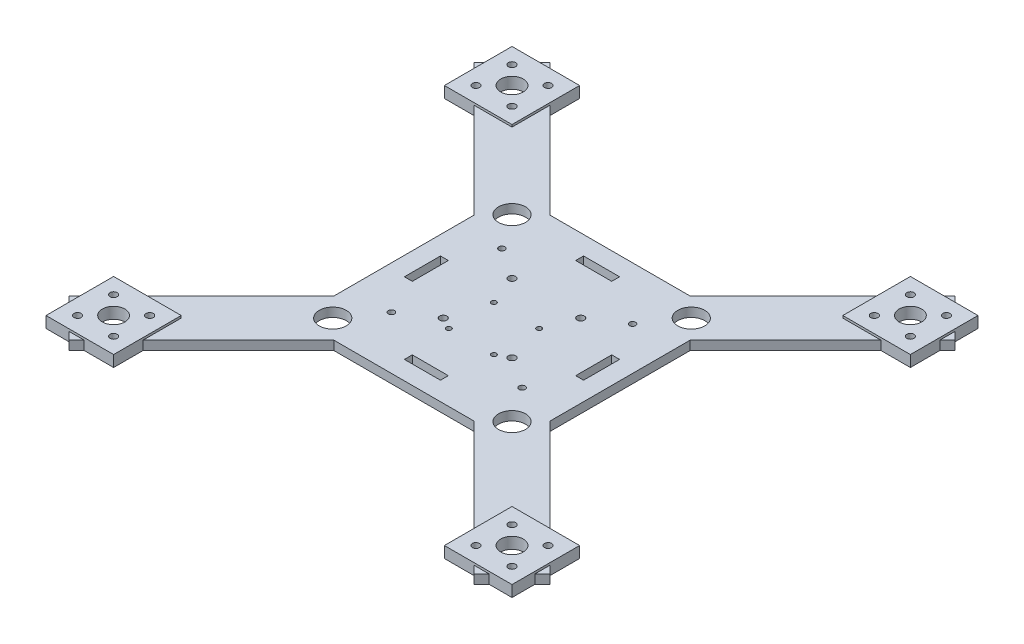
SolidWorks part; units mm, degrees
ref_plane "Front Plane" through (0, 0, 0) normal (0, 0, 1) x (1, 0, 0)
ref_plane "Top Plane" through (0, 0, 0) normal (0, 1, 0) x (1, 0, 0)
ref_plane "Right Plane" through (0, 0, 0) normal (1, 0, 0) x (0, 0, -1)
sketch "Sketch1" plane through (0, 0, 0) normal (0, 1, 0) x (1, 0, 0)
  line L0 (-48, -48) -> (48, -48)
  line L1 (48, -48) -> (48, 48)
  line L2 (48, 48) -> (-48, 48)
  line L3 (-48, 48) -> (-48, -48)
extrude "CenterDeck" add sketch "Sketch1" along normal blind 4
sketch "Sketch2" plane through (0, 0, 0) normal (0, 1, 0) x (1, 0, 0)
  line L0 (22.6274, 39.598) -> (39.598, 22.6274)
  line L1 (39.598, 22.6274) -> (106.7731, 89.8026)
  line L2 (106.7731, 89.8026) -> (89.8026, 106.7731)
  line L3 (89.8026, 106.7731) -> (22.6274, 39.598)
extrude "Arm1" add sketch "Sketch2" along normal blind 4
sketch "Sketch3" plane through (0, 0, 0) normal (0, 1, 0) x (1, 0, 0)
  line L0 (39.598, -22.6274) -> (22.6274, -39.598)
  line L1 (22.6274, -39.598) -> (89.8026, -106.7731)
  line L2 (89.8026, -106.7731) -> (106.7731, -89.8026)
  line L3 (106.7731, -89.8026) -> (39.598, -22.6274)
extrude "Arm2" add sketch "Sketch3" along normal blind 4
sketch "Sketch4" plane through (0, 0, 0) normal (0, 1, 0) x (1, 0, 0)
  line L0 (-39.598, 22.6274) -> (-22.6274, 39.598)
  line L1 (-22.6274, 39.598) -> (-89.8026, 106.7731)
  line L2 (-89.8026, 106.7731) -> (-106.7731, 89.8026)
  line L3 (-106.7731, 89.8026) -> (-39.598, 22.6274)
extrude "Arm3" add sketch "Sketch4" along normal blind 4
sketch "Sketch5" plane through (0, 0, 0) normal (0, 1, 0) x (1, 0, 0)
  line L0 (-22.6274, -39.598) -> (-39.598, -22.6274)
  line L1 (-39.598, -22.6274) -> (-106.7731, -89.8026)
  line L2 (-106.7731, -89.8026) -> (-89.8026, -106.7731)
  line L3 (-89.8026, -106.7731) -> (-22.6274, -39.598)
extrude "Arm4" add sketch "Sketch5" along normal blind 4
sketch "Sketch6" plane through (0, 0, 0) normal (0, 1, 0) x (1, 0, 0)
  line L0 (73.3883, 73.3883) -> (103.3883, 73.3883)
  line L1 (103.3883, 73.3883) -> (103.3883, 103.3883)
  line L2 (103.3883, 103.3883) -> (73.3883, 103.3883)
  line L3 (73.3883, 103.3883) -> (73.3883, 73.3883)
extrude "MotorPad1" add sketch "Sketch6" along normal blind 5
sketch "Sketch7" plane through (0, 0, 0) normal (0, 1, 0) x (1, 0, 0)
  line L0 (73.3883, -103.3883) -> (103.3883, -103.3883)
  line L1 (103.3883, -103.3883) -> (103.3883, -73.3883)
  line L2 (103.3883, -73.3883) -> (73.3883, -73.3883)
  line L3 (73.3883, -73.3883) -> (73.3883, -103.3883)
extrude "MotorPad2" add sketch "Sketch7" along normal blind 5
sketch "Sketch8" plane through (0, 0, 0) normal (0, 1, 0) x (1, 0, 0)
  line L0 (-103.3883, 73.3883) -> (-73.3883, 73.3883)
  line L1 (-73.3883, 73.3883) -> (-73.3883, 103.3883)
  line L2 (-73.3883, 103.3883) -> (-103.3883, 103.3883)
  line L3 (-103.3883, 103.3883) -> (-103.3883, 73.3883)
extrude "MotorPad3" add sketch "Sketch8" along normal blind 5
sketch "Sketch9" plane through (0, 0, 0) normal (0, 1, 0) x (1, 0, 0)
  line L0 (-103.3883, -103.3883) -> (-73.3883, -103.3883)
  line L1 (-73.3883, -103.3883) -> (-73.3883, -73.3883)
  line L2 (-73.3883, -73.3883) -> (-103.3883, -73.3883)
  line L3 (-103.3883, -73.3883) -> (-103.3883, -103.3883)
extrude "MotorPad4" add sketch "Sketch9" along normal blind 5
sketch "Sketch10" plane through (0, 0, 0) normal (0, 1, 0) x (1, 0, 0)
  circle A0 centre (96.3883, 96.3883) radius 1.6
  circle A1 centre (96.3883, 80.3883) radius 1.6
  circle A2 centre (80.3883, 96.3883) radius 1.6
  circle A3 centre (80.3883, 80.3883) radius 1.6
  circle A4 centre (88.3883, 88.3883) radius 5
extrude "MotorHoles1" cut sketch "Sketch10" along normal through all
sketch "Sketch11" plane through (0, 0, 0) normal (0, 1, 0) x (1, 0, 0)
  circle A0 centre (96.3883, -80.3883) radius 1.6
  circle A1 centre (96.3883, -96.3883) radius 1.6
  circle A2 centre (80.3883, -80.3883) radius 1.6
  circle A3 centre (80.3883, -96.3883) radius 1.6
  circle A4 centre (88.3883, -88.3883) radius 5
extrude "MotorHoles2" cut sketch "Sketch11" along normal through all
sketch "Sketch12" plane through (0, 0, 0) normal (0, 1, 0) x (1, 0, 0)
  circle A0 centre (-80.3883, 96.3883) radius 1.6
  circle A1 centre (-80.3883, 80.3883) radius 1.6
  circle A2 centre (-96.3883, 96.3883) radius 1.6
  circle A3 centre (-96.3883, 80.3883) radius 1.6
  circle A4 centre (-88.3883, 88.3883) radius 5
extrude "MotorHoles3" cut sketch "Sketch12" along normal through all
sketch "Sketch13" plane through (0, 0, 0) normal (0, 1, 0) x (1, 0, 0)
  circle A0 centre (-80.3883, -80.3883) radius 1.6
  circle A1 centre (-80.3883, -96.3883) radius 1.6
  circle A2 centre (-96.3883, -80.3883) radius 1.6
  circle A3 centre (-96.3883, -96.3883) radius 1.6
  circle A4 centre (-88.3883, -88.3883) radius 5
extrude "MotorHoles4" cut sketch "Sketch13" along normal through all
sketch "Sketch14" plane through (0, 0, 0) normal (0, 1, 0) x (1, 0, 0)
  circle A0 centre (15.25, 15.25) radius 1.6
  circle A1 centre (15.25, -15.25) radius 1.6
  circle A2 centre (-15.25, 15.25) radius 1.6
  circle A3 centre (-15.25, -15.25) radius 1.6
extrude "StackHoles" cut sketch "Sketch14" along normal through all
sketch "Sketch15" plane through (0, 0, 0) normal (0, 1, 0) x (1, 0, 0)
  circle A0 centre (29, 24.5) radius 1.35
  circle A1 centre (29, -24.5) radius 1.35
  circle A2 centre (-29, 24.5) radius 1.35
  circle A3 centre (-29, -24.5) radius 1.35
extrude "PiHoles" cut sketch "Sketch15" along normal through all
sketch "Sketch16" plane through (0, 0, 0) normal (0, 1, 0) x (1, 0, 0)
  line L0 (-39.75, -8) -> (-36.25, -8)
  line L1 (-36.25, -8) -> (-36.25, 8)
  line L2 (-36.25, 8) -> (-39.75, 8)
  line L3 (-39.75, 8) -> (-39.75, -8)
  line L4 (36.25, -8) -> (39.75, -8)
  line L5 (39.75, -8) -> (39.75, 8)
  line L6 (39.75, 8) -> (36.25, 8)
  line L7 (36.25, 8) -> (36.25, -8)
  line L8 (-8, 36.25) -> (8, 36.25)
  line L9 (8, 36.25) -> (8, 39.75)
  line L10 (8, 39.75) -> (-8, 39.75)
  line L11 (-8, 39.75) -> (-8, 36.25)
  line L12 (-8, -39.75) -> (8, -39.75)
  line L13 (8, -39.75) -> (8, -36.25)
  line L14 (8, -36.25) -> (-8, -36.25)
  line L15 (-8, -36.25) -> (-8, -39.75)
extrude "BattStrapSlots" cut sketch "Sketch16" along normal through all
sketch "Sketch17" plane through (0, 0, 0) normal (0, 1, 0) x (1, 0, 0)
  circle A0 centre (10, 2) radius 1.1
  circle A1 centre (10, -18) radius 1.1
  circle A2 centre (-10, 2) radius 1.1
  circle A3 centre (-10, -18) radius 1.1
extrude "CameraHoles" cut sketch "Sketch17" along normal through all
sketch "Sketch18" plane through (0, 0, 0) normal (0, 1, 0) x (1, 0, 0)
  circle A0 centre (39.7748, 39.7748) radius 6
  circle A1 centre (39.7748, -39.7748) radius 6
  circle A2 centre (-39.7748, 39.7748) radius 6
  circle A3 centre (-39.7748, -39.7748) radius 6
extrude "ArmLightening" cut sketch "Sketch18" along normal through all
